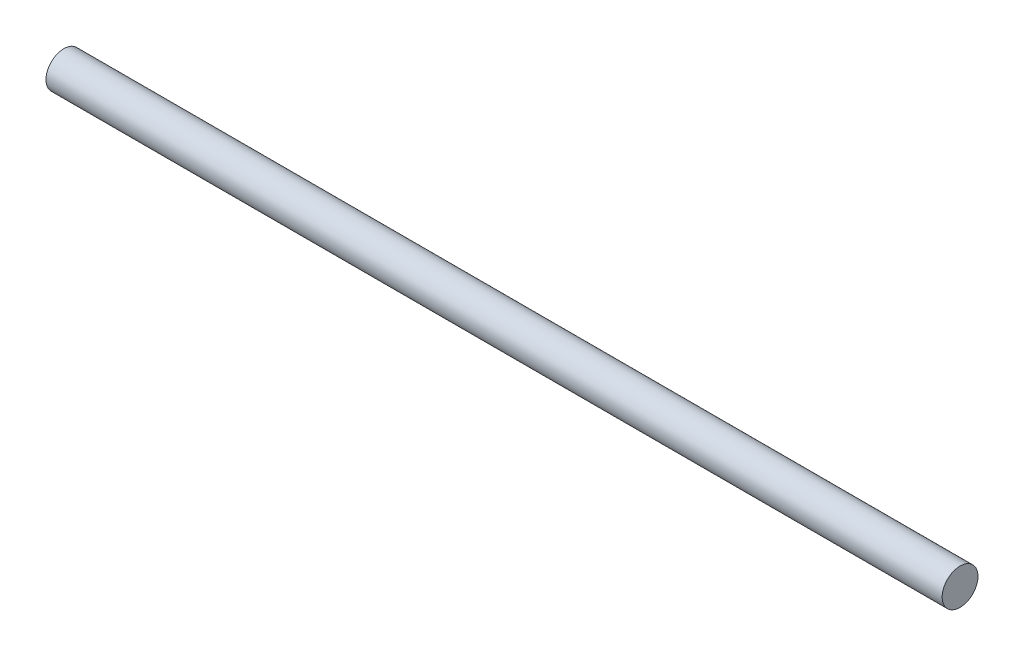
SolidWorks part; units mm, degrees
ref_plane "Front Plane" through (0, 0, 0) normal (0, 0, 1) x (1, 0, 0)
ref_plane "Top Plane" through (0, 0, 0) normal (0, 1, 0) x (1, 0, 0)
ref_plane "Right Plane" through (0, 0, 0) normal (1, 0, 0) x (0, 0, -1)
sketch "Sketch1" plane through (0, 0, 0) normal (1, 0, 0) x (0, 0, -1)
  circle A0 centre (0, 0) radius 4
  dimension "D1" = 8
extrude "Boss-Extrude1" add sketch "Sketch1" along normal blind 200 contours A0
